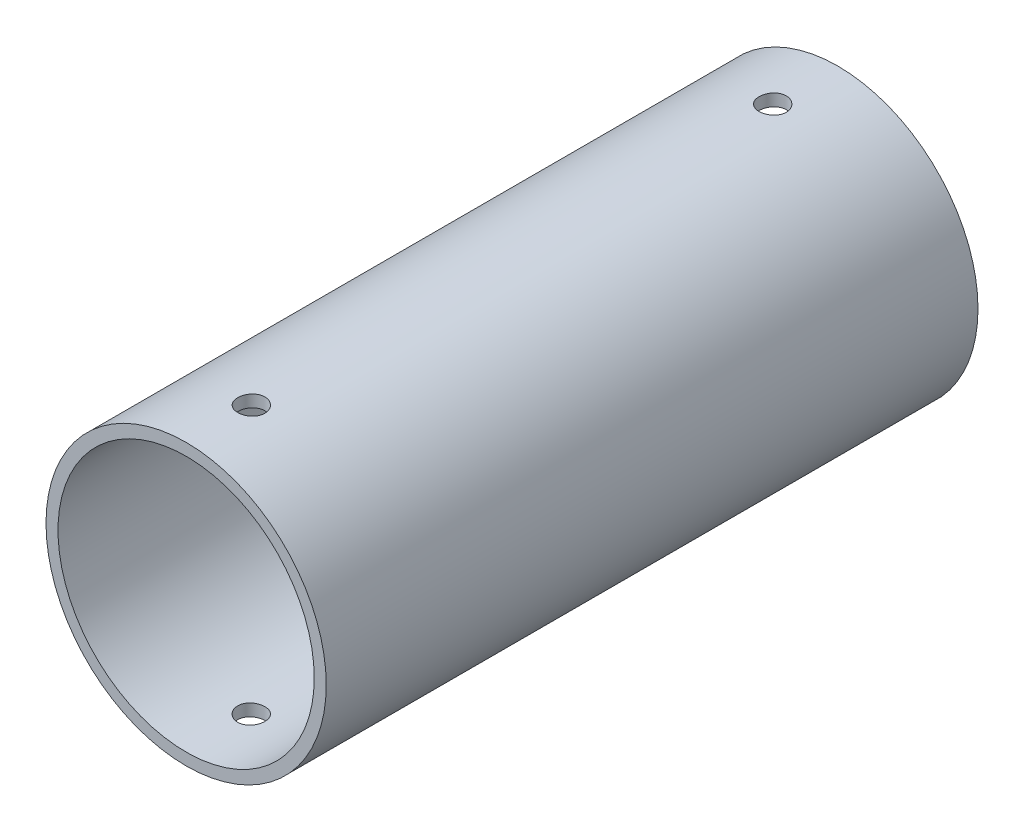
SolidWorks part; units mm, degrees
material "6061-T6 (SS)"
ref_plane "Plano frontal" through (0, 0, 0) normal (0, 0, 1) x (1, 0, 0)
ref_plane "Plano superior" through (0, 0, 0) normal (0, 1, 0) x (1, 0, 0)
ref_plane "Plano direito" through (0, 0, 0) normal (1, 0, 0) x (0, 0, -1)
sketch "Esboço2" plane through (0, 0, 0) normal (0, 0, 1) x (1, 0, 0)
  circle A0 centre (0, 0) radius 25.8
  circle A1 centre (0, 0) radius 23.59
extrude "Ressalto-extrusão1" add sketch "Esboço2" along normal blind 120
sketch "Sketch1" plane through (0, 0, 0) normal (0, 1, 0) x (1, 0, 0)
  line L0 (-25.8, -120) -> (25.8, -120) construction
  line L1 (23.59, 0) -> (-23.59, 0) construction
  circle A0 centre (0, -108) radius 2.5
  circle A1 centre (0, -12) radius 2.5
  dimension "D1" = 12
  dimension "D2" = 12
extrude "Cut-Extrude1" cut sketch "Sketch1" against normal through all both and the other way through all
